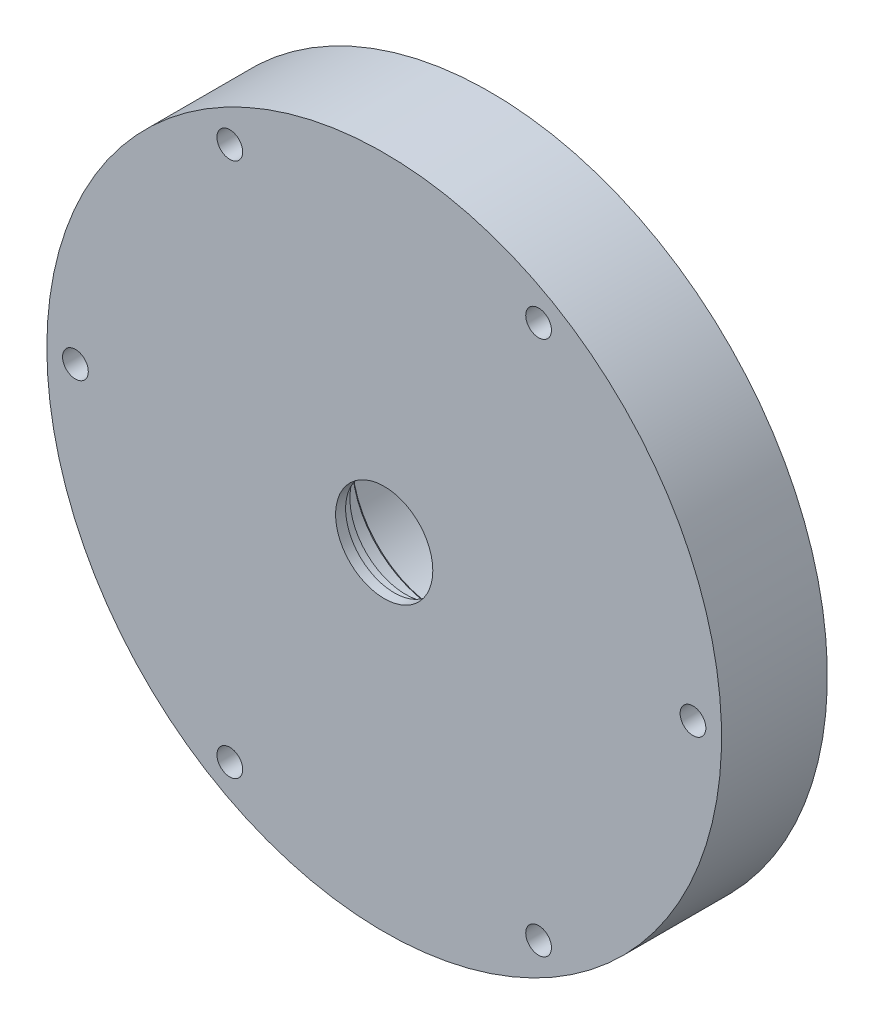
SolidWorks part; units mm, degrees
ref_plane "前视基准面" through (0, 0, 0) normal (0, 0, 1) x (1, 0, 0)
ref_plane "上视基准面" through (0, 0, 0) normal (0, 1, 0) x (1, 0, 0)
ref_plane "右视基准面" through (0, 0, 0) normal (1, 0, 0) x (0, 0, -1)
sketch "草图1" plane through (0, 0, 0) normal (1, 0, 0) x (0, 0, -1)
  line L0 (0, 0) -> (0, 118)
  line L1 (0, 55) -> (0, -55) construction
  line L2 (0, 118) -> (37, 118)
  line L3 (37, 118) -> (37, 95)
  line L4 (37, 95) -> (45, 95)
  line L5 (45, 95) -> (45, 99)
  line L6 (45, 99) -> (48, 99)
  line L7 (48, 99) -> (48, 0)
  line L8 (55, 0) -> (-55, 0) construction
  line L9 (48, 0) -> (0, 0) construction
  line L10 (0, 0) -> (48, 0)
  point P5 (41, 95)
  point P14 (46.5, 99)
  dimension "D1" = 236
  dimension "D2" = 190
  dimension "D3" = 198
  dimension "D4" = 37
  dimension "D5" = 3
  dimension "D6" = 48
revolve "旋转1" add sketch "草图1" angle 360 about L9
sketch "草图2" plane through (0, 0, 0) normal (1, 0, 0) x (0, 0, -1)
  line L0 (26.4, 0) -> (-26.4, 0) construction
  line L1 (0, 0) -> (81.8474, 0) construction
  line L2 (48, 0) -> (48, 91)
  line L3 (48, -99) -> (48, 99) construction
  line L4 (48, 91) -> (11, 91)
  line L5 (11, 91) -> (11, 56)
  line L6 (11, 56) -> (12.5, 56)
  line L7 (12.5, 56) -> (12.5, 45)
  line L8 (12.5, 45) -> (38.75, 45)
  line L9 (38.75, 45) -> (38.75, 0)
  line L10 (38.75, 0) -> (48, 0)
  line L11 (0, 129.8) -> (0, -129.8) construction
  dimension "D1" = 37
  dimension "D2" = 1.5
  dimension "D3" = 90
  dimension "D4" = 182
  dimension "D5" = 112
  dimension "D6" = 38.75
revolve "切除-旋转1" cut sketch "草图2" angle 360 about L1
sketch "草图3" plane through (0, 0, 0) normal (1, 0, 0) x (0, 0, -1)
  line L0 (0, 0) -> (71.3266, 0) construction
  line L1 (45.0161, 0) -> (-45.0161, 0) construction
  line L2 (0, 0) -> (0, 17)
  line L3 (0, 129.8) -> (0, -129.8) construction
  line L4 (0, 17) -> (3.5, 17)
  line L5 (3.5, 17) -> (3.5, 19.5)
  line L6 (3.5, 19.5) -> (7.5, 19.5)
  line L7 (7.5, 19.5) -> (7.5, 30)
  line L8 (7.5, 30) -> (19.75, 30)
  line L9 (19.75, 30) -> (19.75, 36)
  line L10 (19.75, 36) -> (38.75, 36)
  line L11 (38.75, -45) -> (38.75, 45) construction
  line L12 (38.75, 36) -> (38.75, 0)
  line L13 (38.75, 0) -> (0, 0)
  dimension "D1" = 72
  dimension "D2" = 60
  dimension "D3" = 19.5
  dimension "D4" = 17
  dimension "D5" = 4
  dimension "D6" = 12.25
  dimension "D7" = 19
revolve "切除-旋转2" cut sketch "草图3" angle 360 about L0
sketch "草图4" plane through (0, 0, -37) normal (0, 0, -1) x (-1, 0, 0)
  circle A1 centre (0, 0) radius 108 construction
  point P1 (108, 0)
  point P7 (54, -93.5307)
  point P8 (-54, -93.5307)
  point P9 (-108, 0)
  point P10 (-54, 93.5307)
  point P11 (54, 93.5307)
  dimension "D1" = 216
  dimension "D2" = 6
hole_wizard "孔1" positions "草图4" profile "草图5" legacy end condition up to next
sketch "草图5" plane through (-54, 93.5307, -37) normal (1, 0, 0) x (0, 1, 0)
  line L0 (0, 0) -> (0, 37)
  line L1 (0, 37) -> (4.5, 37)
  line L2 (4.5, 37) -> (4.5, 0)
  line L3 (4.5, 0) -> (0, 0)
  line L4 (0, 110) -> (0, -10) construction
  dimension "直径" = 9
  dimension "深度" = 37
chamfer "倒角1" distance 1 angle 45 2 edges at (30, 0, -19.75) (36, 0, -38.75)
